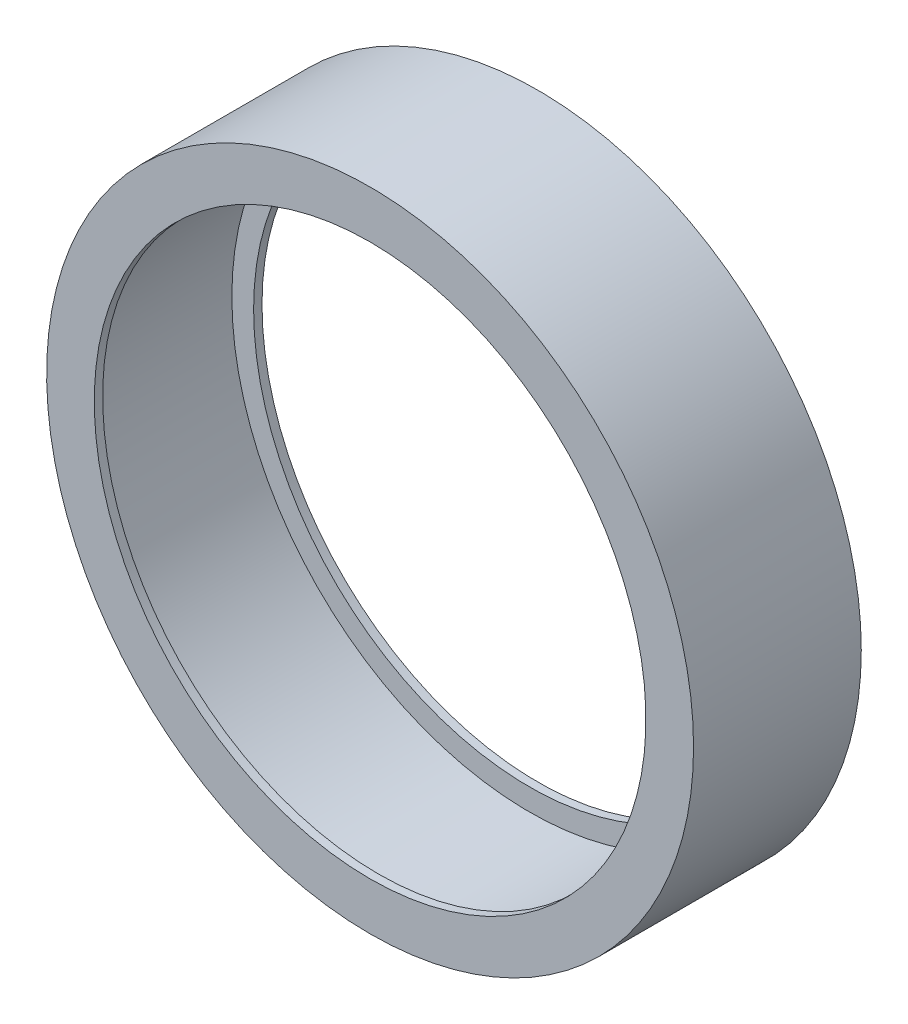
SolidWorks part; units mm, degrees
ref_plane "Front Plane" through (0, 0, 0) normal (0, 0, 1) x (1, 0, 0)
ref_plane "Top Plane" through (0, 0, 0) normal (0, 1, 0) x (1, 0, 0)
ref_plane "Right Plane" through (0, 0, 0) normal (1, 0, 0) x (0, 0, -1)
sketch "Sketch1" plane through (0, 0, 0) normal (0, 0, 1) x (1, 0, 0)
  circle A0 centre (0, 0) radius 125
  circle A1 centre (0, 0) radius 115
  dimension "D1" = 250
  dimension "D2" = 230
extrude "Boss-Extrude1" add sketch "Sketch1" along normal blind 100
sketch "Sketch2" plane through (0, 0, 0) normal (0, 0, -1) x (-1, 0, 0)
  circle A0 centre (0, 0) radius 115
  circle A1 centre (0, 0) radius 106.5913
extrude "Boss-Extrude2" add sketch "Sketch2" against normal blind 5
sketch "Sketch3" plane through (0, 0, 100) normal (0, 0, 1) x (1, 0, 0)
  circle A0 centre (0, 0) radius 106.5913
  circle A1 centre (0, 0) radius 115
extrude "Boss-Extrude3" add sketch "Sketch3" against normal blind 5
scale "Scale1" scale about centroid uniform scaling no x scale factor 1.08 y scale factor 1.08 z scale factor 0.7
